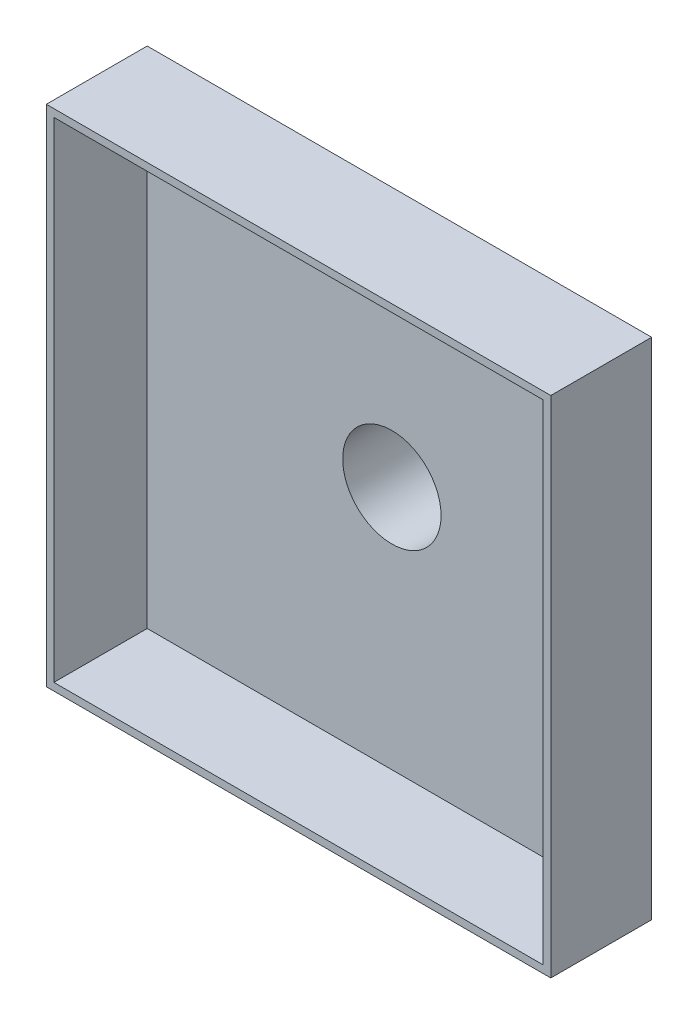
SolidWorks part; units mm, degrees
ref_plane "正面" through (0, 0, 0) normal (0, 0, 1) x (1, 0, 0)
ref_plane "平面" through (0, 0, 0) normal (0, 1, 0) x (1, 0, 0)
ref_plane "右側面" through (0, 0, 0) normal (1, 0, 0) x (0, 0, -1)
sketch "ｽｹｯﾁ1" plane through (0, 0, 0) normal (0, 0, 1) x (1, 0, 0)
  line L1 (-100, 100) -> (100, 100)
  line L2 (-100, 100) -> (-100, -100)
  line L3 (-100, -100) -> (100, -100)
  line L4 (100, 100) -> (100, -100)
  line L5 (-100, 100) -> (100, -100) construction
  line L6 (-100, -100) -> (100, 100) construction
  point P0 (0, 0)
  dimension "D1" = 200
  dimension "D2" = 200
extrude "ﾎﾞｽ - 押し出し1" add sketch "ｽｹｯﾁ1" along normal blind 40
sketch "ｽｹｯﾁ2" plane through (0, 0, 0) normal (0, 0, 1) x (1, 0, 0)
  circle A0 centre (0, 0) radius 22.5
  dimension "D1" = 45
extrude "ﾎﾞｽ - 押し出し2" add sketch "ｽｹｯﾁ2" against normal blind 40
shell "ｼｪﾙ1" thickness 3
